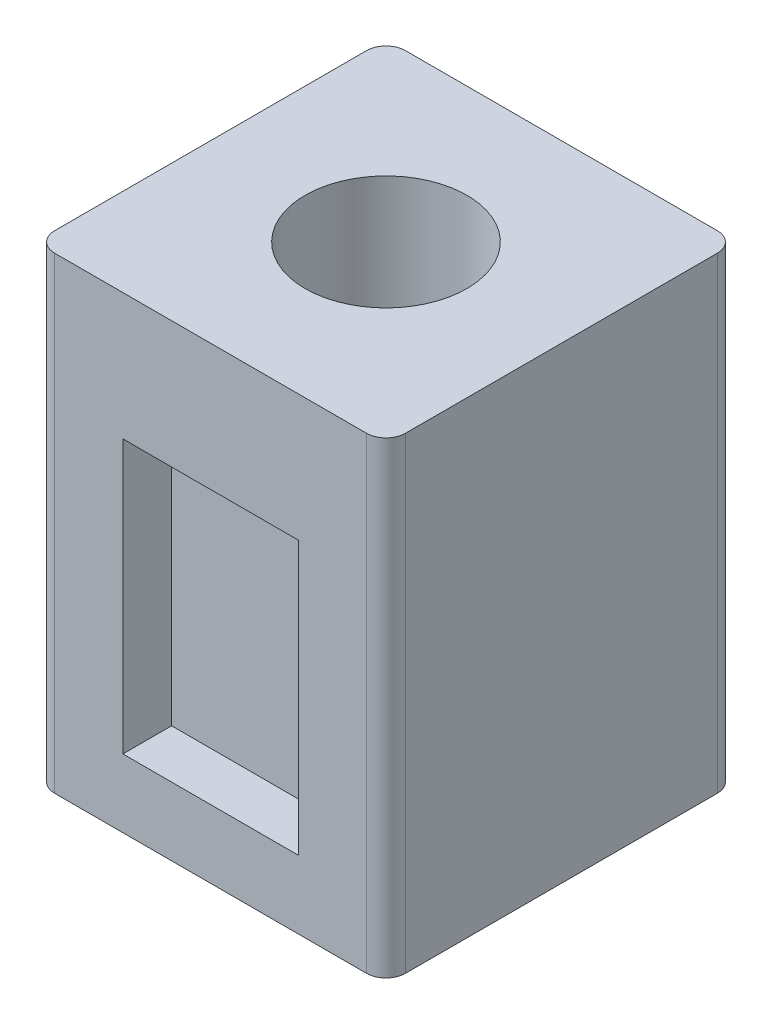
SolidWorks part; units mm, degrees
ref_plane "前视基准面" through (0, 0, 0) normal (0, 0, 1) x (1, 0, 0)
ref_plane "上视基准面" through (0, 0, 0) normal (0, 1, 0) x (1, 0, 0)
ref_plane "右视基准面" through (0, 0, 0) normal (1, 0, 0) x (0, 0, -1)
other "Configuration Table"
sketch "草图1" plane through (0, 0, 0) normal (0, 0, 1) x (1, 0, 0)
  line L0 (0, 0) -> (36, 0)
  line L1 (36, 0) -> (36, 48)
  line L2 (36, 48) -> (0, 48)
  line L3 (0, 48) -> (0, 0)
  dimension "width" = 36
  dimension "height" = 48
extrude "Lift_carriage" add sketch "草图1" along normal blind 36
fillet "Fillet" radius 2 4 edges at (0, 24, 0) (36, 24, 0) (0, 24, 36) (36, 24, 36)
sketch "草图2" plane through (0, 0, 36) normal (0, 0, 1) x (1, 0, 0)
  line L0 (9, 7) -> (27, 7)
  line L1 (27, 7) -> (27, 35)
  line L2 (27, 35) -> (9, 35)
  line L3 (9, 35) -> (9, 7)
  dimension "x0" = 9
  dimension "x1" = 27
  dimension "y0" = 7
  dimension "y2" = 35
extrude "Front_recess" cut sketch "草图2" against normal blind 5
sketch "草图3" plane through (0, 48, 0) normal (0, 1, 0) x (1, 0, 0)
  circle A0 centre (18, -18) radius 8.3
  dimension "diameter" = 16.6
  dimension "x" = 18
  dimension "y" = 18
extrude "Screw_passage" cut sketch "草图3" against normal through all
